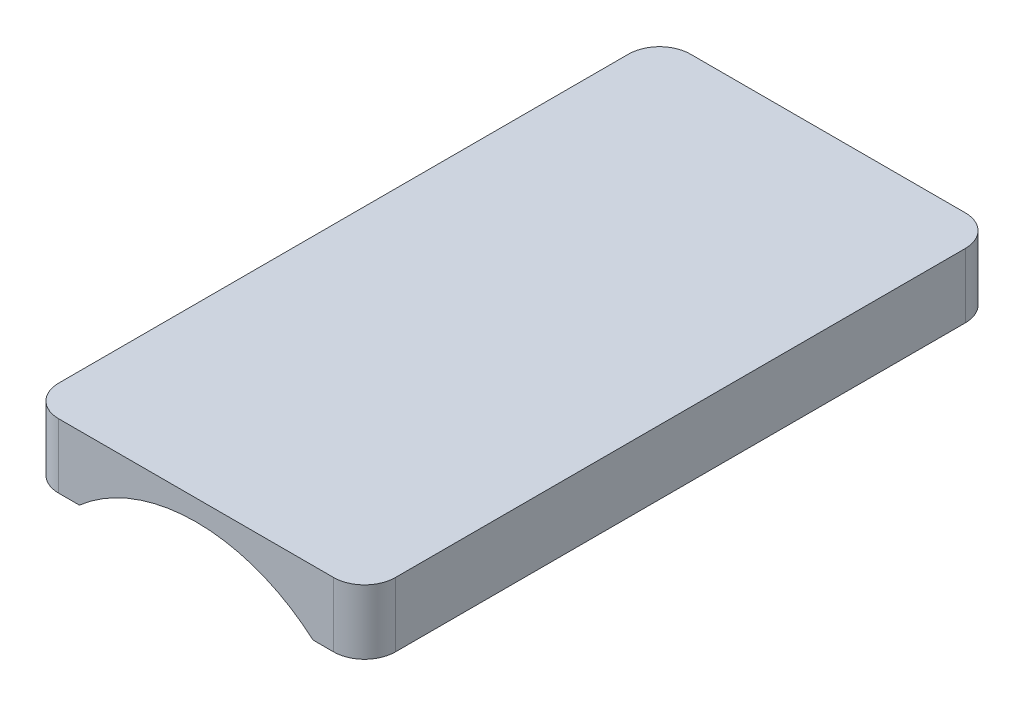
SolidWorks part; units mm, degrees
ref_plane "Front Plane" through (0, 0, 0) normal (0, 0, 1) x (1, 0, 0)
ref_plane "Top Plane" through (0, 0, 0) normal (0, 1, 0) x (1, 0, 0)
ref_plane "Right Plane" through (0, 0, 0) normal (1, 0, 0) x (0, 0, -1)
sketch "Sketch1" plane through (0, 0, 0) normal (1, 0, 0) x (0, 0, -1)
  line L0 (0, 0) -> (0, 6.25)
  line L1 (0, 6.25) -> (61.25, 6.25)
  line L2 (61.25, 6.25) -> (61.25, 0)
  line L3 (61.25, 0) -> (0, 0)
  dimension "D1" = 61.25
  dimension "D2" = 6.25
extrude "Boss-Extrude1" add sketch "Sketch1" along normal blind 32.65
sketch "Sketch2" plane through (0, 0, 0) normal (0, 0, 1) x (1, 0, 0)
  line L0 (32.65, 0) -> (0, 0) construction
  line L1 (5, 0) -> (27.65, 0)
  arc A0 (5, 0) -> (27.65, 0) centre (16.325, -12.9639) cw
  point P3 (16.325, 4.25)
  dimension "D1" = 4.25
  dimension "D2" = 5
  dimension "D3" = 5
extrude "Cut-Extrude1" cut sketch "Sketch2" against normal blind 35 and the other way through all
sketch "Sketch3" plane through (0, 0, -61.25) normal (0, 0, -1) x (-1, 0, 0)
  line L7 (-32.65, 6.25) -> (0, 6.25) construction
  line L12 (-11.175, 0.95) -> (-11.175, 5.3)
  line L13 (-11.175, 5.3) -> (-21.475, 5.3)
  line L15 (-21.475, 0.95) -> (-11.175, 0.95)
  line L16 (-21.475, 0.95) -> (-19.3, 3.125)
  line L17 (-19.3, 3.125) -> (-21.475, 5.3)
  line L18 (-32.65, 0) -> (0, 0) construction
  point P8 (-16.325, 5.3)
  point P9 (-11.175, 3.125)
  point P12 (-16.325, 6.25)
  dimension "D1" = 10.3
  dimension "D2" = 0.95
  dimension "D3" = 0.95
extrude "Cut-Extrude2" cut sketch "Sketch3" against normal blind 10
fillet "Fillet1" radius 3 4 edges at (0, 3.125, 0) (32.65, 3.125, 0) (32.65, 3.125, -61.25) (0, 3.125, -61.25)
